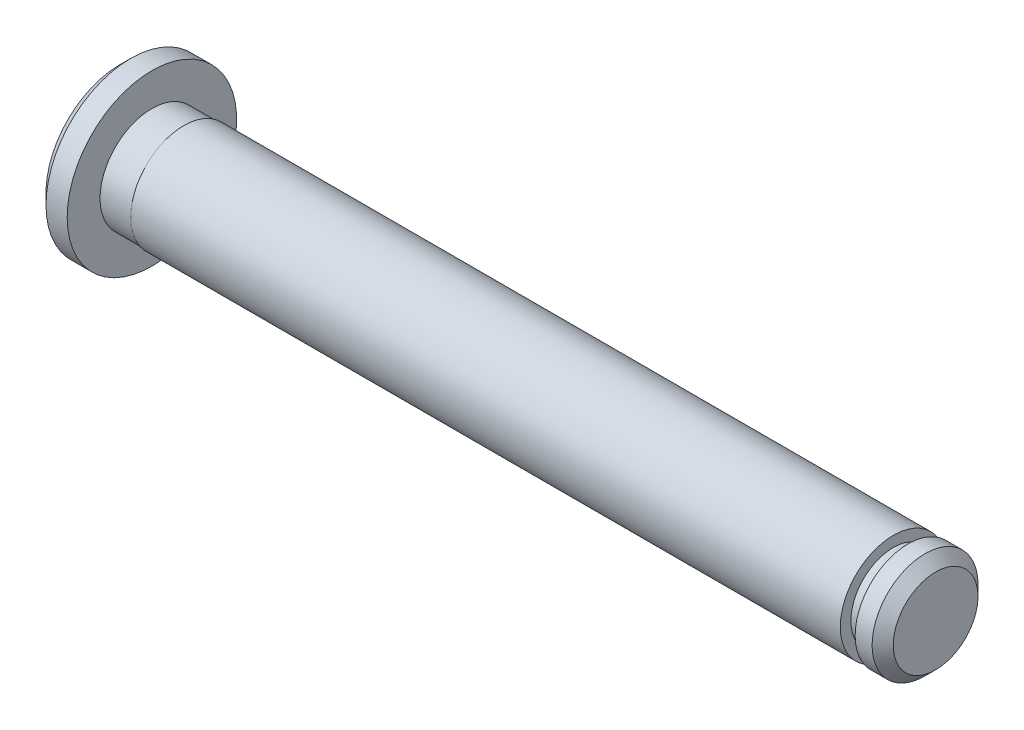
SolidWorks part; units mm, degrees
ref_plane "Front Plane" through (0, 0, 0) normal (0, 0, 1) x (1, 0, 0)
ref_plane "Top Plane" through (0, 0, 0) normal (0, 1, 0) x (1, 0, 0)
ref_plane "Right Plane" through (0, 0, 0) normal (1, 0, 0) x (0, 0, -1)
sketch "Sketch1" plane through (0, 0, 0) normal (0, 0, 1) x (1, 0, 0)
  line L0 (0, 0) -> (37, 0) construction
  line L1 (-1.5, 0) -> (-1.5, 4)
  line L2 (-1.5, 4) -> (0, 4)
  line L3 (0, 4) -> (0, 2.45)
  line L4 (0, 2.45) -> (1.5, 2.45)
  line L5 (37, 2.5) -> (37, 0)
  line L6 (-1.5, 0) -> (37, 0)
  line L7 (1.5, 2.45) -> (1.5, 2.5)
  line L8 (1.5, 2.5) -> (35, 2.5)
  line L9 (35, 2.5) -> (35, 2)
  line L10 (35, 2) -> (35.7, 2)
  line L11 (35.7, 2) -> (35.7, 2.5)
  line L12 (35.7, 2.5) -> (37, 2.5)
  dimension "H" = 8
  dimension "T" = 1.5
  dimension "D" = 5
  dimension "N_s" = 1.5
  dimension "U_s" = 4.9
  dimension "L" = 35
  dimension "M" = 0.7
  dimension "N" = 2
  dimension "D_s" = 4
revolve "Revolve1" add sketch "Sketch1" angle 360 about L0
chamfer "Chamfer1" distance 0.5 angle 45 2 edges at (-1.5, 0, 4) (37, 0, 2.5)
sketch "Sketch2" [suppressed] plane through (0, 0, 0) normal (0, 0, 1) x (1, 0, 0)
  line L0 (-1.5, 2.25) -> (-1.5, -2.25) construction
  line L3 (0, 0) -> (12, 0)
  line L4 (0, 0) -> (0, 1.5)
  line L5 (0, 1.5) -> (12, 1.5)
  line L6 (-1.5, 0) -> (12, 0) construction
  line L7 (12, -1) -> (12, 1) construction
  line L9 (12, 0) -> (12, 1.5)
  dimension "D" = 5
revolve "Cut-Revolve1" [suppressed] cut sketch "Sketch2" angle 360 about L6
sketch "Sketch3" [suppressed] plane through (0, 0, 0) normal (0, 0, 1) x (1, 0, 0)
  line L0 (0, 0) -> (11.5, 0) construction
  line L1 (0, -2.75) -> (0, 2.75) construction
  line L3 (0, 0) -> (0, 1.45)
  line L4 (0, 1.45) -> (1.5, 1.45)
  line L5 (11.5, 1.5) -> (11.5, 0)
  line L6 (0, 0) -> (11.5, 0)
  line L7 (1.5, 1.45) -> (1.5, 1.5)
  line L8 (1.5, 1.5) -> (10, 1.5)
  line L9 (10, 1.5) -> (10, 1)
  line L10 (10, 1) -> (10.5, 1)
  line L11 (10.5, 1) -> (10.5, 1.5)
  line L12 (10.5, 1.5) -> (11.5, 1.5)
  dimension "D" = 5
  dimension "L" = 35
  dimension "D_s" = 4
  dimension "N_s" = 1.5
  dimension "U_s" = 4.9
  dimension "M" = 0.7
  dimension "NC" = 1.5
revolve "Revolve2" [suppressed] add sketch "Sketch3" angle 360 about L0
chamfer "Chamfer2" [suppressed] distance 0.5 angle 45
sketch "Sketch4" [suppressed] plane through (0, 0, 0) normal (0, 0, 1) x (1, 0, 0)
  line L0 (-1.5, 2.25) -> (-1.5, -2.25) construction
  line L1 (-1.5, 2.75) -> (0, 2.75)
  line L2 (-1.5, 2.75) -> (-1.5, 0)
  line L3 (-1.5, 0) -> (0, 0)
  line L4 (0, 2.75) -> (0, 0)
  line L6 (0, -2.75) -> (0, 2.75) construction
  line L7 (0, 0) -> (-1.5, 0) construction
  dimension "H" = 8
revolve "Cut-Revolve2" [suppressed] cut sketch "Sketch4" angle 360 about L7
sketch "Sketch5" [suppressed] plane through (0, 0, 0) normal (0, 0, 1) x (1, 0, 0)
  line L1 (-2, 2.75) -> (0, 2.75)
  line L2 (-2, 2.75) -> (-2, 0)
  line L3 (-2, 0) -> (0, 0)
  line L4 (0, 2.75) -> (0, 0)
  line L7 (0, 0) -> (-2, 0) construction
  dimension "TC" = 2
  dimension "H" = 8
revolve "Revolve3" [suppressed] add sketch "Sketch5" angle 360 about L7
chamfer "Chamfer3" [suppressed] distance 0.5 angle 45
sketch "Sketch6" [suppressed] plane through (0, 0, 0) normal (1, 0, 0) x (0, 0, -1)
  line L0 (0, 0) -> (-2.75, 0) construction
  line L1 (-2.75, 2.75) -> (-1.75, 2.75)
  line L2 (-2.75, 2.75) -> (-2.75, -2.75)
  line L3 (-2.75, -2.75) -> (-1.75, -2.75)
  line L4 (-1.75, 2.75) -> (-1.75, -2.75)
  dimension "HC" = 3
  dimension "D2" = 4
  dimension "H" = 8
extrude "Cut-Extrude1" [suppressed] cut sketch "Sketch6" against normal through all
equation "\"D2@Sketch6\" = \"H@Sketch1\" / 2"
equation "\"HC@Sketch6\"=if ( \"D@Sketch1\" > 10 , \"H@Sketch1\" / 2 - 2 , \"H@Sketch1\" / 2 - 1 )"
